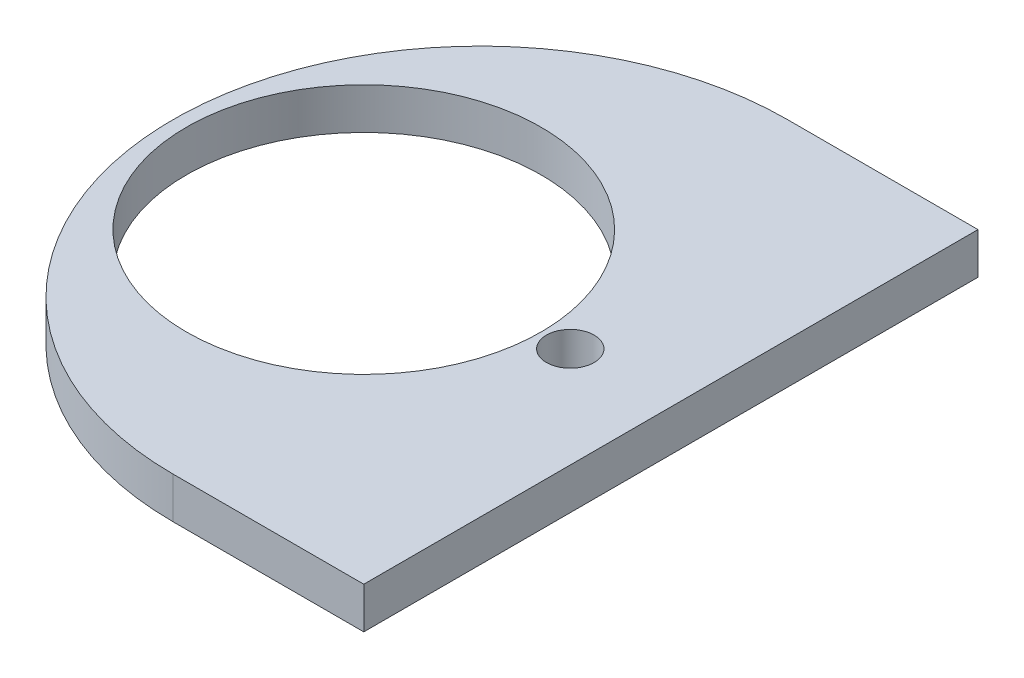
SolidWorks part; units mm, degrees
ref_plane "Front Plane" through (0, 0, 0) normal (0, 0, 1) x (1, 0, 0)
ref_plane "Top Plane" through (0, 0, 0) normal (0, 1, 0) x (1, 0, 0)
ref_plane "Right Plane" through (0, 0, 0) normal (1, 0, 0) x (0, 0, -1)
sketch "Sketch1" plane through (0, 0, 0) normal (0, 1, 0) x (1, 0, 0)
  line L0 (0, 0) -> (36, 0)
  line L1 (36, 0) -> (36, -116)
  line L2 (36, -116) -> (0, -116)
  circle A1 centre (-22, -58) radius 33.5
  arc A3 (0, 0) -> (0, -116) centre (0, -58) ccw
  circle A4 centre (17, -58) radius 4.5
  dimension "D1" = 58
  dimension "D4" = 67
  dimension "D5" = 9
  dimension "D2" = 116
  dimension "D3" = 36
  dimension "D6" = 39
extrude "Boss-Extrude1" add sketch "Sketch1" along normal blind 7.8
